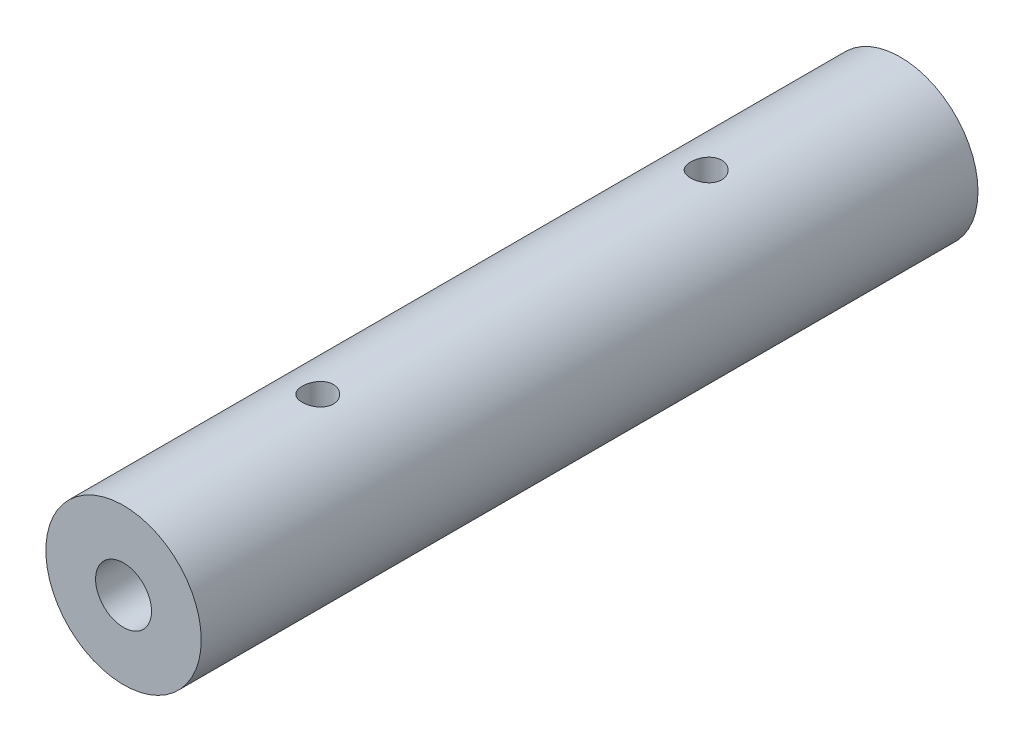
SolidWorks part; units mm, degrees
ref_plane "Front Plane" through (0, 0, 0) normal (0, 0, 1) x (1, 0, 0)
ref_plane "Top Plane" through (0, 0, 0) normal (0, 1, 0) x (1, 0, 0)
ref_plane "Right Plane" through (0, 0, 0) normal (1, 0, 0) x (0, 0, -1)
sketch "Sketch1" plane through (0, 0, 0) normal (0, 0, 1) x (1, 0, 0)
  circle A0 centre (0, 0) radius 6.35
  circle A1 centre (0, 0) radius 2.286
  dimension "D1" = 12.7
  dimension "D2" = 4.572
extrude "Boss-Extrude1" add sketch "Sketch1" along normal mid plane 63.5
sketch "Sketch3" plane through (0, 0, 0) normal (0, 1, 0) x (1, 0, 0)
  circle A0 centre (0, 15.875) radius 1.27
  circle A1 centre (0, -15.875) radius 1.27
  dimension "D1" = 31.75
  dimension "D2" = 15.875
  dimension "D3" = 2.54
  dimension "D4" = 2.54
extrude "Cut-Extrude1" cut sketch "Sketch3" against normal mid plane 63.5
